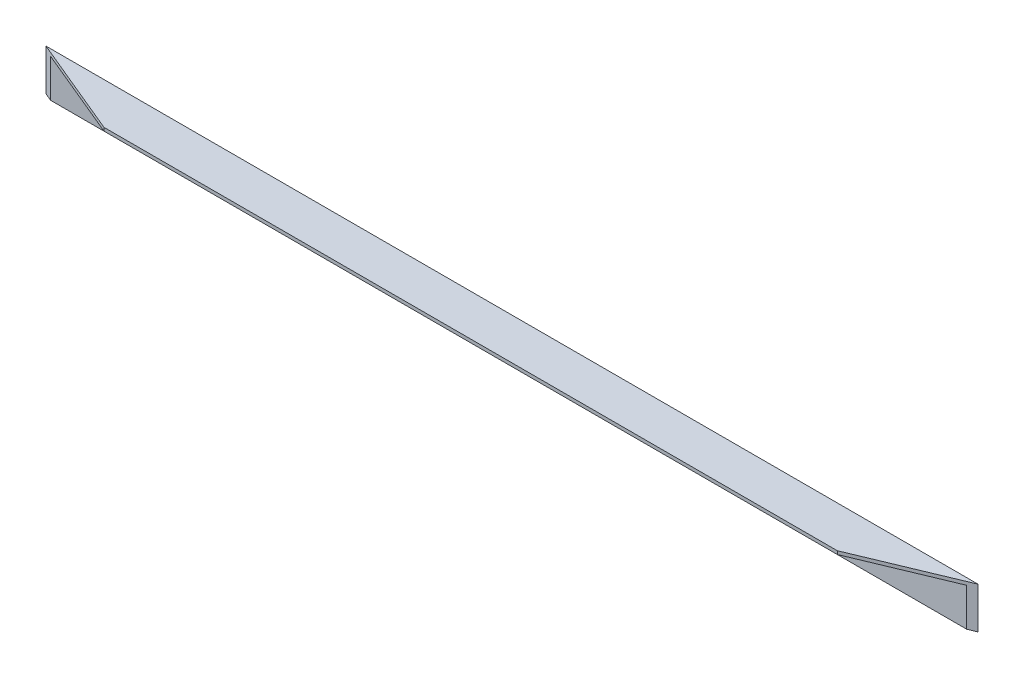
SolidWorks part; units mm, degrees
ref_plane "前视基准面" through (0, 0, 0) normal (0, 0, 1) x (1, 0, 0)
ref_plane "上视基准面" through (0, 0, 0) normal (0, 1, 0) x (1, 0, 0)
ref_plane "右视基准面" through (0, 0, 0) normal (1, 0, 0) x (0, 0, -1)
sketch "草图1" plane through (0, 0, 0) normal (0, 0, 1) x (1, 0, 0)
  line L0 (-1000, 0) -> (49000, 0) construction
  line L1 (-1126, 0) -> (1126, 0)
  line L2 (1126, 0) -> (1126, 100)
  line L3 (1126, 100) -> (-1126, 100)
  line L4 (-531.6366, 50) -> (49468.3634, 50) construction
  line L5 (1086, 100) -> (1086, 0) construction
  line L6 (971, 100) -> (971, 0) construction
  line L7 (0, 100) -> (0, 0.8753) construction
  line L8 (80, 100) -> (80, 0) construction
  line L9 (160, 100) -> (160, 0) construction
  line L10 (-1126, 0) -> (-1126, 100)
  point P42 (0, 0)
  dimension "D7" = 115
  dimension "D1" = 1126
  dimension "D2" = 100
  dimension "D4" = 50
  dimension "D5" = 40
  dimension "D10" = 80
  dimension "D11" = 80
extrude "凸台-拉伸1" add sketch "草图1" along normal blind 8
sketch "草图2" plane through (0, 0, 8) normal (0, 0, 1) x (1, 0, 0)
  line L1 (-1126, 100) -> (1126, 100)
  line L2 (-1126, 100) -> (-1126, 92)
  line L3 (-1126, 92) -> (1126, 92)
  line L4 (1126, 100) -> (1126, 92)
  point P0 (-1126, 100)
  dimension "D1" = 2252
  dimension "D2" = 8
extrude "凸台-拉伸2" add sketch "草图2" along normal blind 92
sketch "草图3" plane through (0, 100, 0) normal (0, 1, 0) x (1, 0, 0)
  line L0 (886, 0) -> (886, -100) construction
  line L1 (1126, 0) -> (-1126, 0) construction
  line L2 (1126, -100) -> (-1126, -100) construction
  line L3 (1126, -100) -> (1126, 0) construction
  line L4 (886, -100) -> (1126, 0)
  line L5 (1126, 0) -> (1126, -100)
  line L6 (1126, -100) -> (886, -100)
  point P8 (1126, 0)
  dimension "D1" = 240
extrude "切除-拉伸3" cut sketch "草图3" against normal through all
mirror "镜向8" about plane through (0, 0, 0) normal (1, 0, 0) of "切除-拉伸3"
